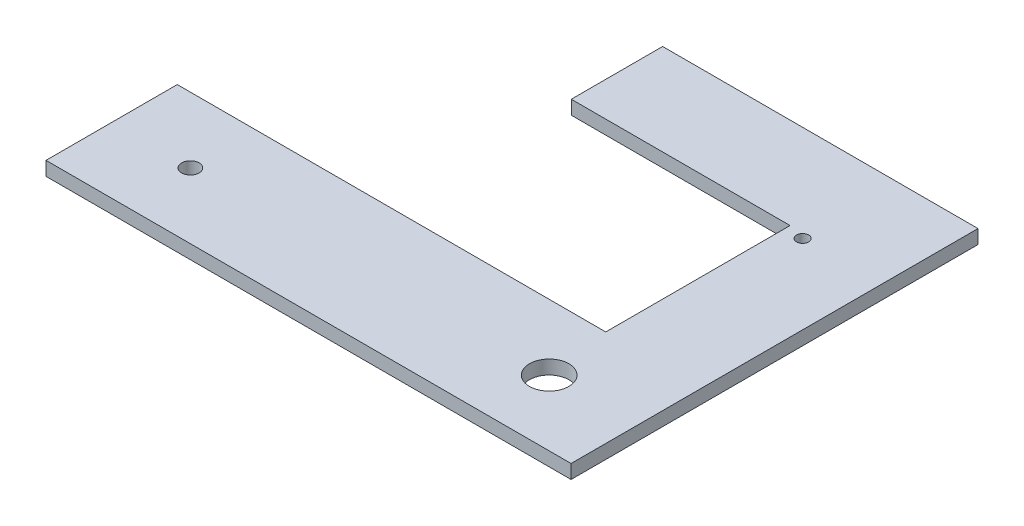
SolidWorks part; units mm, degrees
ref_plane "Front" through (0, 0, 0) normal (0, 0, 1) x (1, 0, 0)
ref_plane "Top" through (0, 0, 0) normal (0, 1, 0) x (1, 0, 0)
ref_plane "Right" through (0, 0, 0) normal (1, 0, 0) x (0, 0, -1)
sketch "Sketch1" plane through (0, 0, 0) normal (0, 1, 0) x (1, 0, 0)
  line L1 (0, 0) -> (120, 0)
  line L2 (0, 0) -> (0, 30)
  line L3 (0, 30) -> (120, 30)
  line L4 (120, 0) -> (120, 30)
  dimension "D1" = 120
  dimension "D2" = 30
extrude "Boss-Extrude1" add sketch "Sketch1" along normal blind 3.175
sketch "Sketch2" plane through (0, 3.175, 0) normal (0, 1, 0) x (1, 0, 0)
  line L0 (0, 30) -> (0, 0) construction
  line L1 (120, 30) -> (0, 30) construction
  line L2 (120, 0) -> (120, 30) construction
  circle A0 centre (18, 15) radius 2
  circle A1 centre (100, 15) radius 4.5
  dimension "D1" = 18
  dimension "D3" = 15
  dimension "D2" = 15
  dimension "D4" = 20
extrude "Cut-Extrude1" cut sketch "Sketch2" against normal blind 3.175
sketch "Sketch3" plane through (0, 0, -30) normal (0, 0, -1) x (-1, 0, 0)
  line L0 (-120, 0) -> (0, 0) construction
  line L1 (-97.9274, 0) -> (-120, 0)
  line L2 (-97.9274, 0) -> (-97.9274, 3.175)
  line L3 (-97.9274, 3.175) -> (-120, 3.175)
  line L4 (-120, 0) -> (-120, 3.175)
  line L5 (-120, 3.175) -> (-120, 0) construction
  line L6 (-120, 3.175) -> (0, 3.175) construction
extrude "Boss-Extrude2" add sketch "Sketch3" along normal blind 63
sketch "Sketch4" plane through (0, 3.175, 0) normal (0, 1, 0) x (1, 0, 0)
  line L0 (97.9274, 93) -> (120, 93) construction
  line L1 (97.9274, 93) -> (97.9274, 30) construction
  circle A0 centre (101.9274, 71) radius 1.3818
  dimension "D1" = 22
  dimension "D2" = 4
extrude "Cut-Extrude2" cut sketch "Sketch4" against normal blind 10
sketch "Sketch5" plane through (97.9274, 0, 0) normal (-1, 0, 0) x (0, 0, 1)
  line L0 (-93, 0) -> (-30, 0) construction
  line L1 (-72.1242, 0) -> (-93, 0)
  line L2 (-72.1242, 0) -> (-72.1242, 3.175)
  line L3 (-72.1242, 3.175) -> (-93, 3.175)
  line L4 (-93, 0) -> (-93, 3.175)
extrude "Boss-Extrude3" add sketch "Sketch5" along normal blind 50
